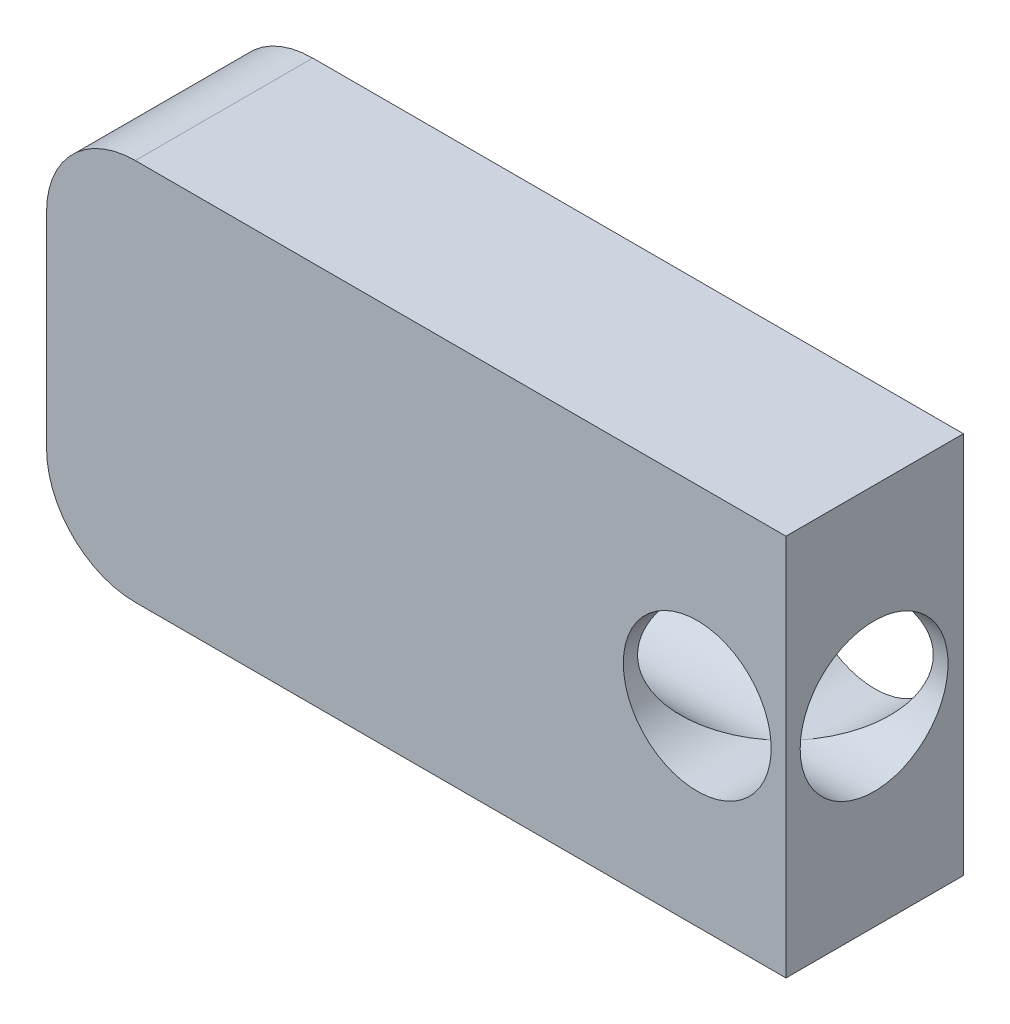
SolidWorks part; units mm, degrees
ref_plane "Front Plane" through (0, 0, 0) normal (0, 0, 1) x (1, 0, 0)
ref_plane "Top Plane" through (0, 0, 0) normal (0, 1, 0) x (1, 0, 0)
ref_plane "Right Plane" through (0, 0, 0) normal (1, 0, 0) x (0, 0, -1)
sketch "Sketch4" plane through (0, 0, 0) normal (0, 0, 1) x (1, 0, 0)
  line L0 (0, 22.0562) -> (0, -21.6672) construction
  line L1 (-9.5, 6.4684) -> (12.5, 6.4684)
  line L2 (-12.5, 3.4684) -> (-12.5, -3.4684)
  line L3 (-9.5, -6.4684) -> (12.5, -6.4684)
  line L4 (12.5, 6.4684) -> (12.5, -6.4684)
  line L5 (-12.5, 6.4684) -> (12.5, -6.4684) construction
  line L6 (-12.5, -6.4684) -> (12.5, 6.4684) construction
  arc A0 (-12.5, -3.4684) -> (-9.5, -6.4684) centre (-9.5, -3.4684) ccw
  arc A1 (-9.5, 6.4684) -> (-12.5, 3.4684) centre (-9.5, 3.4684) ccw
  circle A5 centre (9.5, 0) radius 2.5
  point P0 (0, 0)
  dimension "D3" = 3
  dimension "D1" = 25
  dimension "D2" = 12.9369
extrude "Boss-Extrude2" add sketch "Sketch4" along normal blind 6
sketch "Sketch5" plane through (-12.5, 0, 0) normal (-1, 0, 0) x (0, 0, 1)
  circle A0 centre (3.0197, 0) radius 2.5
  point P0 (3.0197, 0)
extrude "Cut-Extrude1" cut sketch "Sketch5" against normal through all
